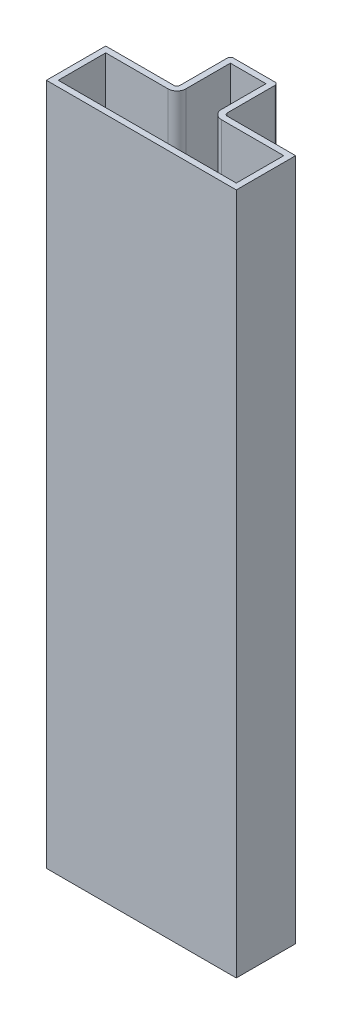
SolidWorks part; units mm, degrees
ref_plane "Front Plane" through (0, 0, 0) normal (0, 0, 1) x (1, 0, 0)
ref_plane "Top Plane" through (0, 0, 0) normal (0, 1, 0) x (1, 0, 0)
ref_plane "Right Plane" through (0, 0, 0) normal (1, 0, 0) x (0, 0, -1)
sketch "Sketch1" plane through (0, 0, 0) normal (0, 1, 0) x (1, 0, 0)
  line L0 (0, 0) -> (32, 0)
  line L1 (32, 0) -> (32, 10)
  line L2 (32, 10) -> (20, 10)
  line L3 (20, 10) -> (20, 19)
  line L4 (20, 19) -> (12, 19)
  line L5 (12, 19) -> (12, 10)
  line L6 (12, 10) -> (0, 10)
  line L7 (0, 10) -> (0, 0)
  dimension "D1" = 10
  dimension "D2" = 8
  dimension "D3" = 12
  dimension "D4" = 9
extrude "Boss-Extrude1" add sketch "Sketch1" along normal blind 115
fillet "Fillet1" radius 0.5 4 edges at (12, 57.5, -10) (20, 57.5, -10) (12, 57.5, -19) (20, 57.5, -19)
shell "Shell1" thickness 1
sketch "Sketch2" plane through (0, 0, 0) normal (0, -1, 0) x (1, 0, 0)
  line L0 (0, -5) -> (32, -5) construction
  line L1 (0, -10) -> (0, 0) construction
  line L2 (32, 0) -> (32, -10) construction
  line L4 (14.5, -3) -> (17.5, -3)
  line L5 (14.5, -3) -> (14.5, -7)
  line L6 (14.5, -7) -> (17.5, -7)
  line L7 (17.5, -3) -> (17.5, -7)
  line L8 (14.5, -3) -> (17.5, -7) construction
  line L9 (14.5, -7) -> (17.5, -3) construction
  point P6 (16, -5)
  dimension "D1" = 3
  dimension "D2" = 4
extrude "Cut-Extrude1" cut sketch "Sketch2" against normal blind 3
